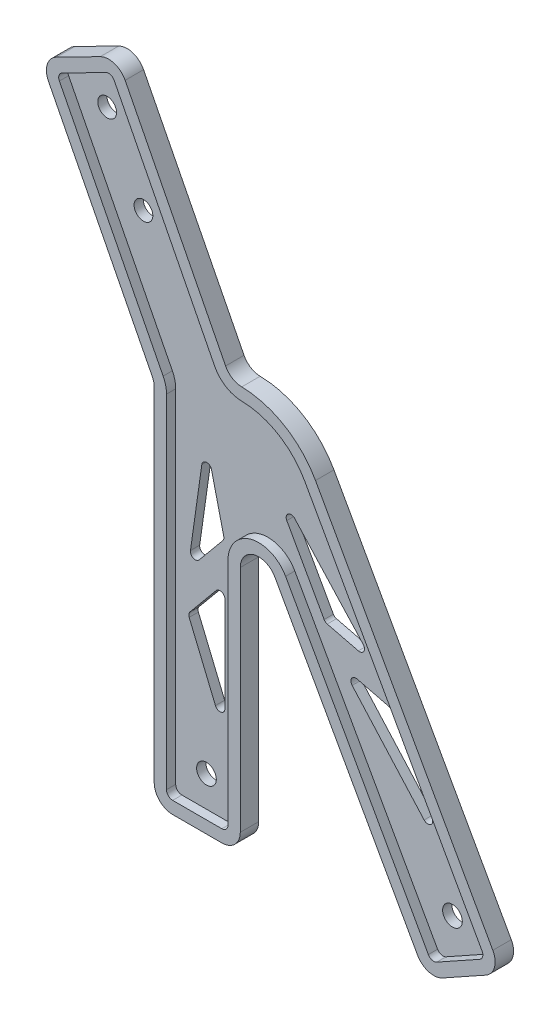
SolidWorks part; units mm, degrees
ref_plane "Piano frontale" through (0, 0, 0) normal (0, 0, 1) x (1, 0, 0)
ref_plane "Piano superiore" through (0, 0, 0) normal (0, 1, 0) x (1, 0, 0)
ref_plane "Piano destro" through (0, 0, 0) normal (1, 0, 0) x (0, 0, -1)
sketch "Schizzo1" plane through (0, 0, 0) normal (0, 0, 1) x (1, 0, 0)
  line L0 (24.8598, 72.2692) -> (24.8598, 64.136) construction
  line L1 (35.424, 75.3104) -> (27.901, 75.3104) construction
  line L2 (38.4652, 65.3753) -> (38.4652, 72.2692) construction
  line L3 (19.3201, 59.2171) -> (14.402, 59.2171) construction
  line L4 (79.5779, 59.2171) -> (47.7896, 59.2171) construction
  line L5 (9.5392, 51.6024) -> (20.0564, 26.3839) construction
  line L6 (24.8598, 72.2692) -> (24.8598, 64.136)
  line L7 (35.424, 75.3104) -> (27.901, 75.3104)
  line L8 (38.4652, 65.3753) -> (38.4652, 72.2692)
  line L9 (19.3201, 59.2171) -> (14.402, 59.2171)
  line L10 (79.5779, 59.2171) -> (47.7896, 59.2171)
  line L11 (9.5392, 51.6024) -> (20.0564, 26.3839)
  circle A0 centre (17.8355, 52.4568) radius 1.6 construction
  circle A1 centre (57.8355, 52.4568) radius 1.6 construction
  circle A2 centre (17.8355, 52.4568) radius 1.6
  circle A3 centre (57.8355, 52.4568) radius 1.6
  circle A4 centre (53.5286, 55.0838) radius 1.6 construction
  circle A5 centre (62.0658, 49.8765) radius 1.6 construction
  circle A6 centre (13.5679, 53.3113) radius 1.6 construction
  circle A7 centre (22.103, 51.6024) radius 1.6 construction
  circle A8 centre (53.5286, 55.0838) radius 1.6
  circle A9 centre (62.0658, 49.8765) radius 1.6
  circle A10 centre (13.5679, 53.3113) radius 1.6
  circle A11 centre (22.103, 51.6024) radius 1.6
sketch "Schizzo2" plane through (0, 0, 0) normal (0, 0, 1) x (1, 0, 0)
  line L0 (22.103, 51.6024) -> (13.5679, 53.3113) construction
  line L1 (1.6887, 138.2484) -> (7.5906, 126.6653) construction
  line L2 (10.8355, 45.4568) -> (10.8355, 104.8781)
  line L3 (1.6887, 138.2484) -> (-28.3966, 202.7666) construction
  line L4 (14.402, 59.2171) -> (246.1332, 167.2752) construction
  line L5 (79.5779, 59.2171) -> (47.7896, 59.2171) construction
  line L6 (1.6887, 138.2484) -> (-1.4892, 144.4854) construction
  line L7 (17.8355, 45.4568) -> (17.8355, 87.1016) construction
  line L8 (-7.7262, 141.3075) -> (10.8355, 104.8781)
  line L9 (10.8355, 45.4568) -> (24.8355, 45.4568)
  line L10 (24.8355, 45.4568) -> (24.8355, 97.296)
  line L11 (67.3576, 49.7495) -> (37.0649, 104.1108)
  line L12 (24.8355, 45.4568) -> (17.8355, 52.4568) construction
  line L13 (-7.7262, 141.3075) -> (4.7479, 147.6634)
  line L14 (1.6887, 138.2484) -> (4.7479, 147.6634) construction
  line L15 (24.8355, 97.296) -> (55.1282, 42.9347)
  line L16 (57.8355, 52.4568) -> (41.9431, 80.9761) construction
  line L17 (57.8355, 52.4568) -> (55.1282, 42.9347) construction
  line L18 (4.7479, 147.6634) -> (23.3199, 111.2137)
  line L19 (55.1282, 42.9347) -> (67.3576, 49.7495)
  line L20 (24.8598, 72.2692) -> (24.8598, 64.136) construction
  line L21 (24.8355, 97.296) -> (37.0649, 104.1108) construction
  circle A0 centre (17.8355, 52.4568) radius 1.6 construction
  circle A1 centre (57.8355, 52.4568) radius 1.6 construction
  circle A2 centre (17.8355, 52.4568) radius 1.6
  circle A3 centre (57.8355, 52.4568) radius 1.6
  circle A4 centre (1.6887, 138.2484) radius 1.525
  circle A5 centre (7.5906, 126.6653) radius 1.525
  arc A7 (37.0649, 104.1108) -> (23.3199, 111.2137) centre (24.8355, 97.296) ccw
  point P3 (4.6397, 132.4568)
  dimension "D5" = 3.05
  dimension "D6" = 13
  dimension "D7" = 14
  dimension "D8" = 80
  dimension "D1" = 25
  dimension "D2" = 2
  dimension "D3" = 45
  dimension "D4" = 45
  dimension "D9" = 45
  dimension "D10" = 14
extrude "Estrusione-Estrusione1" add sketch "Schizzo2" along normal blind 1.5
fillet "Raccordo1" radius 3 9 edges at (24.8355, 97.296, 0.75) (55.1282, 42.9347, 0.75) (24.8355, 45.4568, 0.75) (-7.7262, 141.3075, 0.75) (4.7479, 147.6634, 0.75) (10.8355, 104.8781, 0.75) (10.8355, 45.4568, 0.75) (67.3576, 49.7495, 0.75) (23.3199, 111.2137, 0.75)
sketch "Schizzo3" plane through (0, 0, 0) normal (0, 0, -1) x (-1, 0, 0)
  line L0 (-58.0329, 58.2656) -> (-47.7601, 76.7004)
  line L1 (-47.7601, 76.7004) -> (-39.7991, 78.6606)
  line L2 (-39.7991, 78.6606) -> (-58.0329, 58.2656)
  line L3 (-45.0995, 81.475) -> (-37.1385, 83.4352)
  line L4 (-37.1385, 83.4352) -> (-27.5762, 100.595)
  line L5 (-27.5762, 100.595) -> (-45.0995, 81.475)
  line L6 (-14.8355, 73.5133) -> (-20.8355, 59.0806)
  line L7 (-20.8355, 59.0806) -> (-20.8355, 80.7548)
  line L8 (-20.8355, 80.7548) -> (-14.8355, 73.5133)
  line L9 (-20.7369, 86.9053) -> (-17.6753, 99.8118)
  line L10 (-17.6753, 99.8118) -> (-14.8355, 79.7828)
  line L11 (-14.8355, 79.7828) -> (-20.7369, 86.9053)
  line L12 (-24.8355, 48.4568) -> (-24.8355, 85.7493) construction
  line L13 (-65.8972, 52.3701) -> (-37.0649, 104.1108) construction
  line L14 (-30.456, 87.2097) -> (-53.6678, 45.5553) construction
  line L15 (-10.8355, 104.1579) -> (-10.8355, 48.4568) construction
  line L16 (-30.456, 87.2097) -> (-53.6678, 45.5553) construction
  dimension "D1" = 4
  dimension "D2" = 4
  dimension "D3" = 4
  dimension "D4" = 4
  dimension "D5" = 4
  dimension "D6" = 4
  dimension "D7" = 4
  dimension "D8" = 4
  dimension "D9" = 4
extrude "Taglio-Estrusione1" cut sketch "Schizzo3" against normal through all
sketch "Schizzo4" plane through (0, 0, 1.5) normal (0, 0, -1) x (-1, 0, 0)
  line L0 (-35.3178, 103.1372) -> (-64.1502, 51.3966)
  line L1 (-63.7634, 50.0363) -> (-56.7752, 46.1421)
  line L2 (-55.4149, 46.5289) -> (-32.2031, 88.1832)
  line L3 (-22.8355, 85.7493) -> (-22.8355, 48.4568)
  line L4 (-21.8355, 47.4568) -> (-13.8355, 47.4568)
  line L5 (-12.8355, 48.4568) -> (-12.8355, 104.1579)
  line L6 (-12.2905, 106.4278) -> (4.5823, 139.5425)
  line L7 (4.1452, 140.8875) -> (-2.9828, 144.5194)
  line L8 (-4.3278, 144.0824) -> (-20.6625, 112.0237)
  line L9 (5.0532, 142.6695) -> (-2.0748, 146.3014)
  line L10 (-6.1098, 144.9903) -> (-22.4445, 112.9317)
  line L11 (-37.0649, 104.1108) -> (-65.8972, 52.3701)
  line L12 (-64.737, 48.2892) -> (-57.7487, 44.3951)
  line L13 (-53.6678, 45.5553) -> (-30.456, 87.2097)
  line L14 (-24.8355, 85.7493) -> (-24.8355, 48.4568)
  line L15 (-21.8355, 45.4568) -> (-13.8355, 45.4568)
  line L16 (-10.8355, 48.4568) -> (-10.8355, 104.1579)
  line L17 (-10.5085, 105.5199) -> (6.3643, 138.6345)
  line L18 (5.0532, 142.6695) -> (-2.0748, 146.3014)
  line L19 (-6.1098, 144.9903) -> (-22.4445, 112.9317)
  line L20 (-37.0649, 104.1108) -> (-65.8972, 52.3701)
  line L21 (-64.737, 48.2892) -> (-57.7487, 44.3951)
  line L22 (-53.6678, 45.5553) -> (-30.456, 87.2097)
  line L23 (-24.8355, 85.7493) -> (-24.8355, 48.4568)
  line L24 (-21.8355, 45.4568) -> (-13.8355, 45.4568)
  line L25 (-10.8355, 48.4568) -> (-10.8355, 104.1579)
  line L26 (-10.5085, 105.5199) -> (6.3643, 138.6345)
  arc A0 (-64.1502, 51.3966) -> (-63.7634, 50.0363) centre (-63.2767, 50.9098) ccw
  arc A1 (-56.7752, 46.1421) -> (-55.4149, 46.5289) centre (-56.2884, 47.0156) ccw
  arc A2 (-22.8355, 85.7493) -> (-32.2031, 88.1832) centre (-27.8355, 85.7493) ccw
  arc A3 (-22.8355, 48.4568) -> (-21.8355, 47.4568) centre (-21.8355, 48.4568) ccw
  arc A4 (-13.8355, 47.4568) -> (-12.8355, 48.4568) centre (-13.8355, 48.4568) ccw
  arc A5 (-12.2905, 106.4278) -> (-12.8355, 104.1579) centre (-7.8355, 104.1579) ccw
  arc A6 (4.5823, 139.5425) -> (4.1452, 140.8875) centre (3.6912, 139.9965) ccw
  arc A7 (-2.9828, 144.5194) -> (-4.3278, 144.0824) centre (-3.4368, 143.6284) ccw
  arc A8 (-25.0346, 109.2943) -> (-20.6625, 112.0237) centre (-25.1176, 114.2936) ccw
  arc A9 (-25.0346, 109.2943) -> (-35.3178, 103.1372) centre (-24.8355, 97.296) ccw
  arc A10 (-2.0748, 146.3014) -> (-6.1098, 144.9903) centre (-3.4368, 143.6284) ccw
  arc A11 (-25.0678, 111.2941) -> (-22.4445, 112.9317) centre (-25.1176, 114.2936) ccw
  arc A12 (-25.0678, 111.2941) -> (-37.0649, 104.1108) centre (-24.8355, 97.296) ccw
  arc A13 (-65.8972, 52.3701) -> (-64.737, 48.2892) centre (-63.2767, 50.9098) ccw
  arc A14 (-57.7487, 44.3951) -> (-53.6678, 45.5553) centre (-56.2884, 47.0156) ccw
  arc A15 (-24.8355, 85.7493) -> (-30.456, 87.2097) centre (-27.8355, 85.7493) ccw
  arc A16 (-24.8355, 48.4568) -> (-21.8355, 45.4568) centre (-21.8355, 48.4568) ccw
  arc A17 (-13.8355, 45.4568) -> (-10.8355, 48.4568) centre (-13.8355, 48.4568) ccw
  arc A18 (-10.5085, 105.5199) -> (-10.8355, 104.1579) centre (-7.8355, 104.1579) ccw
  arc A19 (6.3643, 138.6345) -> (5.0532, 142.6695) centre (3.6912, 139.9965) ccw
  arc A20 (-2.0748, 146.3014) -> (-6.1098, 144.9903) centre (-3.4368, 143.6284) ccw
  arc A21 (-25.0678, 111.2941) -> (-22.4445, 112.9317) centre (-25.1176, 114.2936) ccw
  arc A22 (-25.0678, 111.2941) -> (-37.0649, 104.1108) centre (-24.8355, 97.296) ccw
  arc A23 (-65.8972, 52.3701) -> (-64.737, 48.2892) centre (-63.2767, 50.9098) ccw
  arc A24 (-57.7487, 44.3951) -> (-53.6678, 45.5553) centre (-56.2884, 47.0156) ccw
  arc A25 (-24.8355, 85.7493) -> (-30.456, 87.2097) centre (-27.8355, 85.7493) ccw
  arc A26 (-24.8355, 48.4568) -> (-21.8355, 45.4568) centre (-21.8355, 48.4568) ccw
  arc A27 (-13.8355, 45.4568) -> (-10.8355, 48.4568) centre (-13.8355, 48.4568) ccw
  arc A28 (-10.5085, 105.5199) -> (-10.8355, 104.1579) centre (-7.8355, 104.1579) ccw
  arc A29 (6.3643, 138.6345) -> (5.0532, 142.6695) centre (3.6912, 139.9965) ccw
  dimension "D1" = 0
  dimension "D2" = 2
extrude "Estrusione-Estrusione2" add sketch "Schizzo4" against normal blind 1.5
fillet "Raccordo2" radius 0.8 12 edges at (17.6753, 99.8118, 0.75) (20.8355, 80.7548, 0.75) (14.8355, 73.5133, 0.75) (14.8355, 79.7828, 0.75) (20.7369, 86.9053, 0.75) (20.8355, 59.0806, 0.75) (58.0329, 58.2656, 0.75) (39.7991, 78.6606, 0.75) (47.7601, 76.7004, 0.75) (27.5762, 100.595, 0.75) (37.1385, 83.4352, 0.75) (45.0995, 81.475, 0.75)
